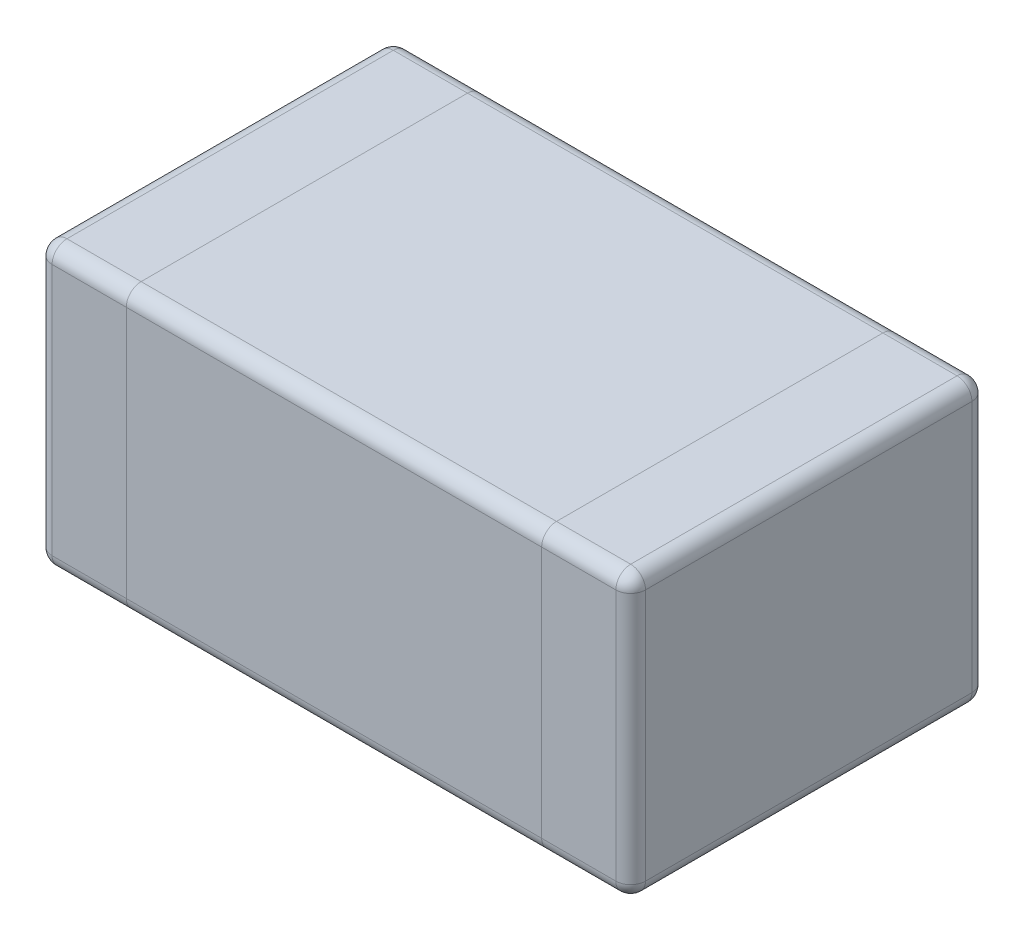
SolidWorks part; units mm, degrees
ref_plane "Front Plane" through (0, 0, 0) normal (0, 0, 1) x (1, 0, 0)
ref_plane "Top Plane" through (0, 0, 0) normal (0, 1, 0) x (1, 0, 0)
ref_plane "Right Plane" through (0, 0, 0) normal (1, 0, 0) x (0, 0, -1)
sketch "Sketch1" plane through (0, 0, 0) normal (0, 1, 0) x (1, 0, 0)
  line L1 (-1, -0.6) -> (1, -0.6)
  line L2 (-1, -0.6) -> (-1, 0.6)
  line L3 (-1, 0.6) -> (1, 0.6)
  line L4 (1, -0.6) -> (1, 0.6)
  line L5 (-1, -0.6) -> (1, 0.6) construction
  line L6 (-1, 0.6) -> (1, -0.6) construction
  point P0 (0, 0)
  dimension "D1" = 2
  dimension "D2" = 1.2
extrude "Extrude1" add sketch "Sketch1" along normal blind 0.95
fillet "Fillet1" radius 0.05 12 edges at (1, 0.475, -0.6) (-1, 0.475, -0.6) (-1, 0.475, 0.6) (1, 0.475, 0.6) (0, 0.95, 0.6) (-1, 0.95, 0) (0, 0.95, -0.6) (1, 0.95, 0) (0, 0, -0.6) (-1, 0, 0) (0, 0, 0.6) (1, 0, 0)
sketch "Sketch2" plane through (0, 0, 0) normal (0, 1, 0) x (1, 0, 0)
  line L0 (-0.95, 0.6) -> (0.95, 0.6) construction
  line L1 (-0.7, -0.6) -> (0.7, -0.6)
  line L2 (-0.7, -0.6) -> (-0.7, 0.6)
  line L3 (-0.7, 0.6) -> (0.7, 0.6)
  line L4 (0.7, -0.6) -> (0.7, 0.6)
  line L5 (0.95, -0.6) -> (-0.95, -0.6) construction
  line L6 (0, 0.55) -> (0, -0.6635) construction
  line L7 (0.95, 0.55) -> (-0.95, 0.55) construction
  line L9 (-1, -0.55) -> (-1, 0.55) construction
  dimension "D1" = 0.3
split line "Split Line3"
